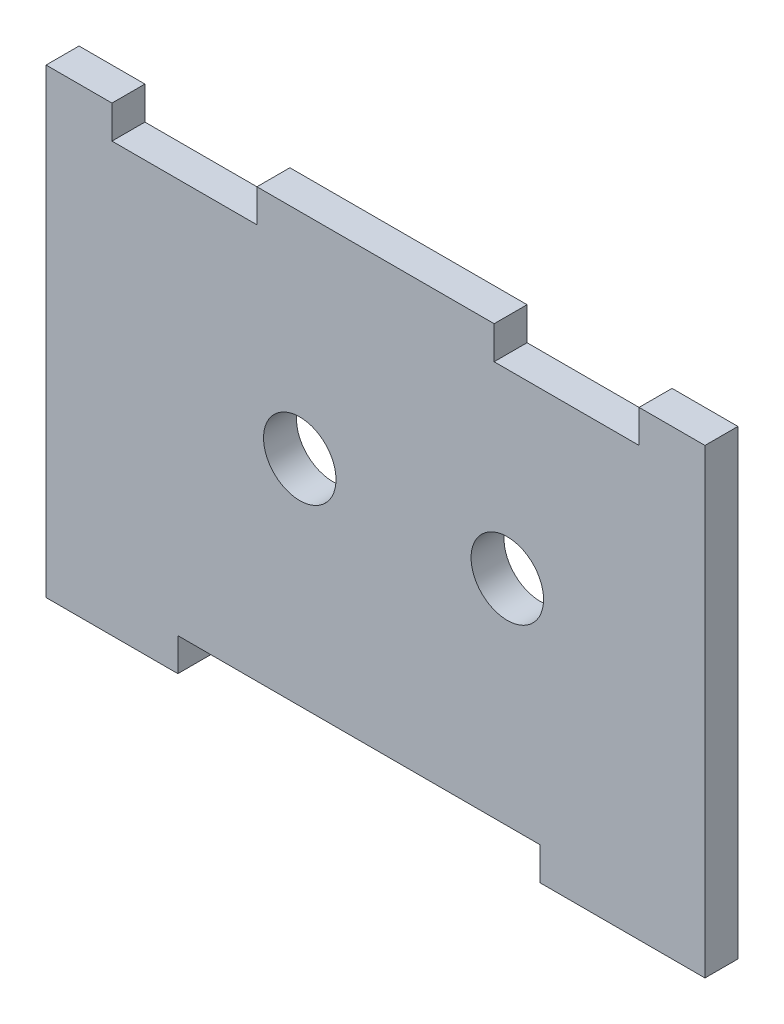
SolidWorks part; units mm, degrees
ref_plane "Front Plane" through (0, 0, 0) normal (0, 0, 1) x (1, 0, 0)
ref_plane "Top Plane" through (0, 0, 0) normal (0, 1, 0) x (1, 0, 0)
ref_plane "Right Plane" through (0, 0, 0) normal (1, 0, 0) x (0, 0, -1)
sketch "Sketch1" plane through (0, 0, 0) normal (0, 0, 1) x (1, 0, 0)
  line L0 (0, 0) -> (0, 82.55)
  line L1 (0, 82.55) -> (-127, 82.55)
  line L2 (-127, 82.55) -> (-127, 0)
  line L3 (-127, 0) -> (0, 0)
  circle A0 centre (-38.1, 41.275) radius 6.985
  circle A1 centre (-78.105, 41.275) radius 6.985
  circle A2 centre (-78.105, 41.275) radius 30.48 construction
  circle A3 centre (-38.1, 41.275) radius 9.525 construction
  dimension "D1" = 13.97
  dimension "D2" = 13.97
  dimension "D6" = 60.96
  dimension "D7" = 19.05
  dimension "D3" = 38.1
  dimension "D4" = 40.005
  dimension "D5" = 41.275
  dimension "D8" = 82.55
  dimension "D9" = 127
extrude "Boss-Extrude1" add sketch "Sketch1" along normal blind 6.35
sketch "Sketch2" plane through (0, 0, 0) normal (0, 0, -1) x (-1, 0, 0)
  line L1 (0, 0) -> (31.75, 0)
  line L2 (0, 0) -> (0, -6.35)
  line L3 (0, -6.35) -> (31.75, -6.35)
  line L4 (31.75, 0) -> (31.75, -6.35)
  line L5 (127, 0) -> (101.6, 0)
  line L6 (127, 0) -> (127, -6.35)
  line L7 (127, -6.35) -> (101.6, -6.35)
  line L8 (101.6, 0) -> (101.6, -6.35)
  dimension "D1" = 6.35
  dimension "D2" = 31.75
  dimension "D3" = 25.4
  dimension "D4" = 6.35
extrude "Boss-Extrude2" add sketch "Sketch2" against normal blind 6.35
sketch "Sketch3" plane through (0, 0, 0) normal (0, 0, -1) x (-1, 0, 0)
  line L0 (0, 82.55) -> (127, 82.55) construction
  line L1 (12.7, 82.55) -> (40.64, 82.55)
  line L2 (12.7, 82.55) -> (12.7, 76.2)
  line L3 (12.7, 76.2) -> (40.64, 76.2)
  line L4 (40.64, 82.55) -> (40.64, 76.2)
  line L5 (0, -6.35) -> (0, 82.55) construction
  line L6 (114.3, 82.55) -> (86.36, 82.55)
  line L7 (114.3, 82.55) -> (114.3, 76.2)
  line L8 (114.3, 76.2) -> (86.36, 76.2)
  line L9 (86.36, 82.55) -> (86.36, 76.2)
  line L10 (127, 82.55) -> (127, -6.35) construction
  dimension "D1" = 12.7
  dimension "D2" = 27.94
  dimension "D3" = 6.35
  dimension "D4" = 6.35
  dimension "D5" = 27.94
  dimension "D6" = 12.7
extrude "Cut-Extrude1" cut sketch "Sketch3" against normal blind 6.35
equation "\"D4@Sketch1\"=(.75+2.4)/2"
